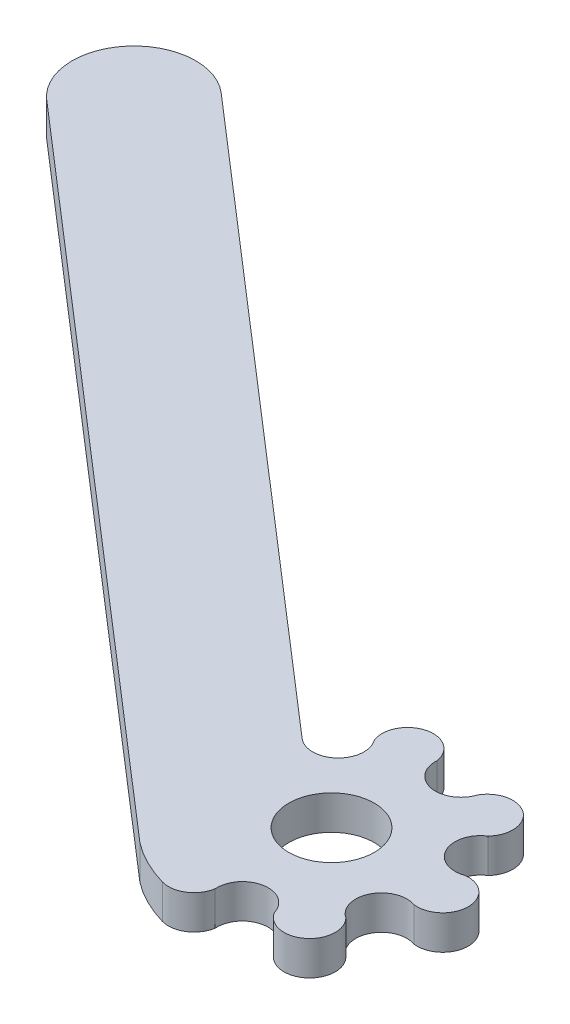
SolidWorks part; units mm, degrees
ref_plane "Спереди" through (0, 0, 0) normal (0, 0, 1) x (1, 0, 0)
ref_plane "Сверху" through (0, 0, 0) normal (0, 1, 0) x (1, 0, 0)
ref_plane "Справа" through (0, 0, 0) normal (1, 0, 0) x (0, 0, -1)
sketch "Эскиз1" plane through (0, 0, 0) normal (0, 1, 0) x (1, 0, 0)
  line L1 (-5.374, 3.6566) -> (-40.4558, 34.0004)
  line L2 (-4.8138, -6.3896) -> (-45.1868, 28.5308)
  circle A0 centre (0, 0) radius 5 construction
  arc A1 (-4.8138, -6.3896) -> (-2.2073, -7.6895) centre (0, 0) ccw
  circle A2 centre (0, 0) radius 6.5 construction
  arc A3 (6.3269, -1.49) -> (6.3269, 1.49) centre (6.5, 0) ccw
  arc A4 (-0.3131, 6.4925) -> (-3.1775, 5.6704) centre (-1.7931, 6.2478) ccw
  arc A5 (4.9971, 4.1568) -> (6.3269, 1.49) centre (5.8169, 2.9006) ccw
  arc A6 (4.9971, 4.1568) -> (2.617, 5.9499) centre (3.9112, 5.1916) ccw
  arc A7 (2.617, -5.9499) -> (4.9971, -4.1568) centre (3.9112, -5.1916) ccw
  arc A8 (-0.3131, 6.4925) -> (2.617, 5.9499) centre (1.1834, 6.3914) ccw
  arc A10 (-5.374, 3.6566) -> (-3.1775, 5.6704) centre (-4.3927, 4.7911) ccw
  arc A12 (6.3269, -1.49) -> (4.9971, -4.1568) centre (5.8169, -2.9006) ccw
  arc A13 (-40.4558, 34.0004) -> (-45.1868, 28.5308) centre (-42.8213, 31.2656) ccw
  arc A14 (2.617, -5.9499) -> (-0.3136, -6.4924) centre (1.1829, -6.3896) ccw
  arc A16 (-2.2073, -7.6895) -> (-0.3136, -6.4924) centre (-1.7935, -6.2477) ccw
  point P8 (6.3269, 1.49)
  point P9 (3.9112, 5.1916)
  point P10 (2.617, -5.9499)
  point P11 (5.8169, 2.9006)
  point P14 (4.9971, 4.1568)
  point P18 (2.617, 5.9499)
  point P21 (1.1834, 6.3914)
  point P23 (1.1829, -6.3896)
  point P24 (-0.3131, 6.4925)
  point P28 (-1.7931, 6.2478)
  point P31 (-3.1775, 5.6704)
  point P33 (-0.3136, -6.4924)
  point P34 (-4.3927, 4.7911)
  point P36 (-6.0691, 2.3273)
  point P37 (5.8169, -2.9006)
  point P42 (3.9112, -5.1916)
  point P44 (-1.7935, -6.2477)
  point P49 (-42.8213, 31.2656)
extrude "Бобышка-Вытянуть1" add sketch "Эскиз1" along normal blind 2 contours L2 A13 L1 A10 A4 A8 A6 A5 A3 A12 A7 A14 A16 A1
sketch "Эскиз2" plane through (0, 2, 0) normal (0, 1, 0) x (1, 0, 0)
  circle A0 centre (0, 0) radius 2.5
  point P0 (0, 0)
extrude "Вырез-Вытянуть1" cut sketch "Эскиз2" against normal through all
